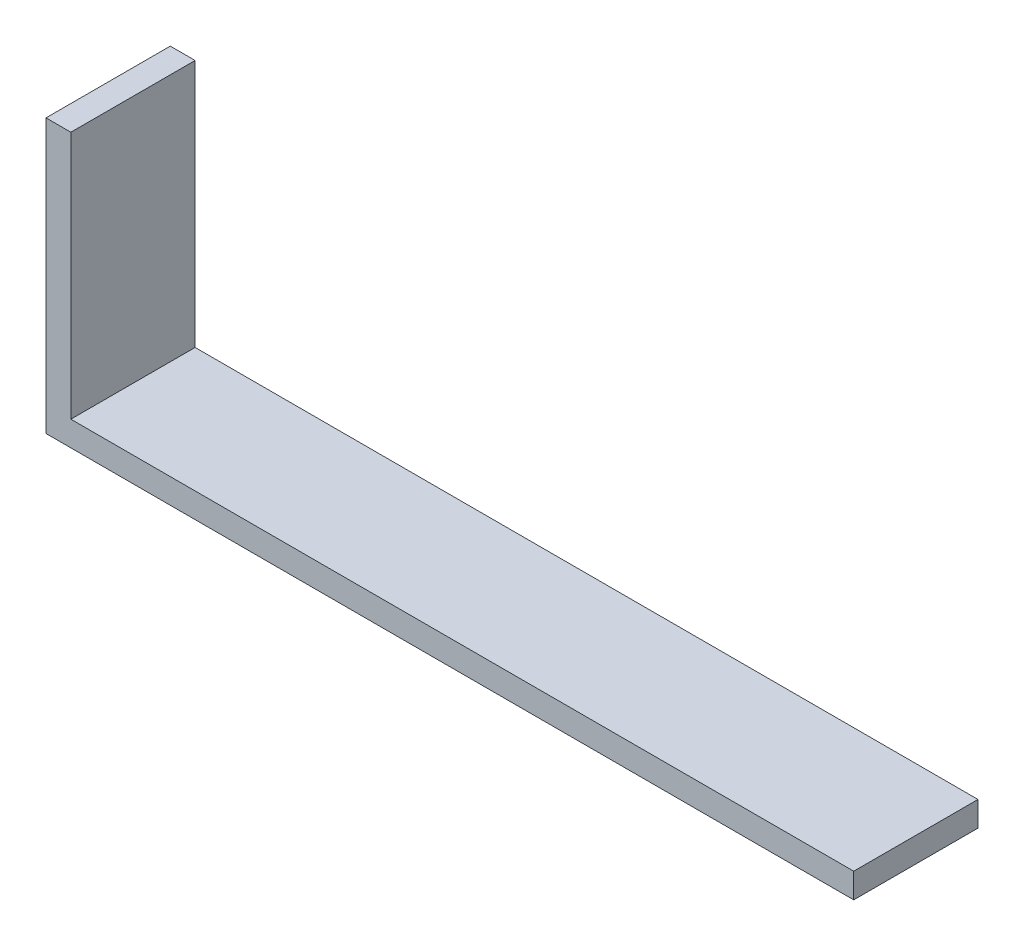
SolidWorks part; units mm, degrees
ref_plane "Front Plane" through (0, 0, 0) normal (0, 0, 1) x (1, 0, 0)
ref_plane "Top Plane" through (0, 0, 0) normal (0, 1, 0) x (1, 0, 0)
ref_plane "Right Plane" through (0, 0, 0) normal (1, 0, 0) x (0, 0, -1)
sketch "Sketch1" plane through (0, 0, 0) normal (0, 0, 1) x (1, 0, 0)
  line L0 (0, 5.9813) -> (0, -7.9887)
  line L1 (0, -7.9887) -> (41.275, -7.9887)
  line L2 (41.275, -7.9887) -> (41.275, -6.7187)
  line L3 (41.275, -6.7187) -> (1.27, -6.7187)
  line L4 (1.27, -6.7187) -> (1.27, 5.9813)
  line L5 (1.27, 5.9813) -> (0, 5.9813)
  dimension "D1" = 12.7
  dimension "D2" = 40.005
  dimension "D3" = 12.7
  dimension "D4" = 1.27
  dimension "D5" = 1.27
  dimension "D6" = 41.275
extrude "Boss-Extrude1" add sketch "Sketch1" along normal blind 6.35
